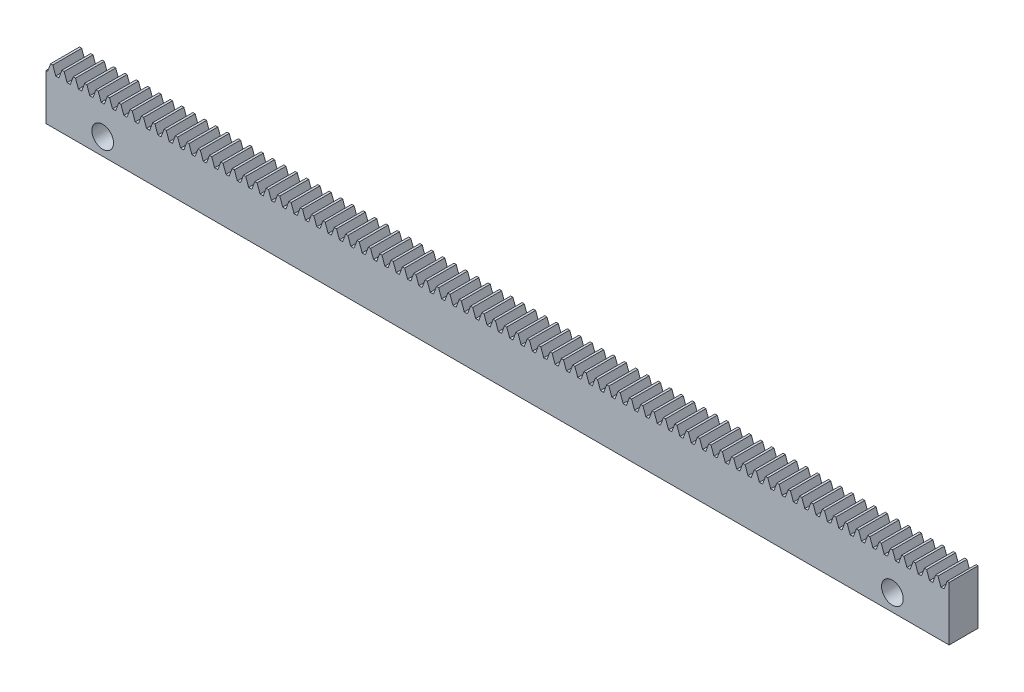
SolidWorks part; units mm, degrees
extrude "Blank" add sketch "BlankSke" against normal blind 4
sketch "BlankSke" plane through (0, 0, 0) normal (0, 0, 1) x (1, 0, 0)
  line L1 (0, 0) -> (125, 0)
  line L2 (0, 0) -> (0, 7.5)
  line L3 (0, 7.5) -> (125, 7.5)
  line L4 (125, 0) -> (125, 7.5)
  dimension "Length" = 125
  dimension "Blank_height" = 7.5
ref_plane "Plane1" through (0, 0, 0) normal (0, 0, 1) x (1, 0, 0)
ref_plane "Plane2" through (0, 0, 0) normal (0, 1, 0) x (1, 0, 0)
ref_plane "Plane3" through (0, 0, 0) normal (1, 0, 0) x (0, 0, -1)
sketch "HoldingSke" plane through (0, 0, 0) normal (0, 1, 0) x (1, 0, 0)
  line L0 (0, 0) -> (0.2783, 1.9805)
  line L1 (-15, 0) -> (100, 0) construction
  line L2 (0, 0) -> (-2.1039, 2.3779)
  line L3 (0, 0) -> (-11.863, 4.5341)
  line L4 (0, 0) -> (1.351, 8.5297)
  line L5 (0, 0) -> (-23.7986, -8.8762)
  line L6 (0, 0) -> (-10.5278, -7.1032)
  line L9 (-71.009, 38.7566) -> (46.4526, 81.5091)
  line L10 (-76.2, 2.8779) -> (-69.2, 2.8779)
  line L11 (0, 0) -> (-4, 0)
  line L12 (-76.2, 101.6) -> (-76.181, 101.6)
  line L13 (24.9733, 27.94) -> (52.9518, 28.4284)
  line L14 (24.9733, 27.94) -> (24.9743, 27.94)
  line L15 (24.9733, 27.94) -> (100.4006, 29.5858)
  circle A0 centre (0, 0) radius 19.05
  circle A1 centre (0, 0) radius 3.5
  circle A2 centre (0, 0) radius 12.7
  dimension "MPH" = 7
  dimension "Diameter" = 38.1
  dimension "Num_teeth" = 81
  dimension "Pitch" = 2
  dimension "Show_teeth" = 998
  dimension "Thickness" = 12.7
  dimension "Ap" = 20
  dimension "Pitch_height" = 7
  dimension "Width" = 4
  dimension "Backlash" = 0.019
  dimension "Addendum_fac" = 1
  dimension "Dedendum_fac" = 1.25
  dimension "Clearance_fac" = 0.25
  dimension "Dedendum_add" = 0.001
  dimension "Length" = 125
  dimension "Module" = 0.5
sketch "TooCutSkeIll" plane through (0, 0, 0) normal (0, 0, 1) x (1, 0, 0)
  line L0 (-0.6269, 7.4868) -> (-0.2524, 6.4579)
  line L1 (-0.134, 6.375) -> (0.134, 6.375)
  line L2 (0.2524, 6.4579) -> (0.6269, 7.4868)
  line L3 (125, 7.5) -> (0, 7.5) construction
  line L4 (0, 0) -> (0, 64.897) construction
  line L5 (-13.208, 7) -> (12.954, 7) construction
  line L6 (0, 0) -> (125, 0) construction
  line L7 (0.4497, 7) -> (0.4497, 48.7463) construction
  line L8 (-0.4497, 7) -> (-0.4497, 48.7463) construction
  line L9 (0.6457, 7.5) -> (0.6457, 7.5254)
  line L10 (-0.6457, 7.5) -> (-0.6457, 7.5254)
  line L11 (-0.6457, 7.5254) -> (0.6457, 7.5254)
  arc A0 (0.134, 6.375) -> (0.2524, 6.4579) centre (0.134, 6.501) ccw
  arc A1 (-0.2524, 6.4579) -> (-0.134, 6.375) centre (-0.134, 6.501) ccw
  arc A2 (0.6457, 7.5) -> (0.6269, 7.4868) centre (0.6457, 7.48) ccw
  arc A3 (-0.6269, 7.4868) -> (-0.6457, 7.5) centre (-0.6457, 7.48) ccw
  dimension "Pitch_height" = 7
  dimension "Addendum_plus" = 0.5254
  dimension "Pressure_angle" = 20
  dimension "Gap_width" = 0.8994
  dimension "Dedendum" = 0.625
extrude "ToothCutIll" [suppressed] cut sketch "TooCutSkeIll" against normal through all
sketch "TooCutSkeSim" plane through (0, 0, 0) normal (0, 0, 1) x (1, 0, 0)
  line L0 (0.2222, 6.375) -> (-0.2222, 6.375)
  line L1 (0.6409, 7.5254) -> (0.2222, 6.375)
  line L2 (0, 17.4625) -> (0, 53.467) construction
  line L3 (0.6409, 7.5254) -> (-0.6409, 7.5254)
  line L6 (-0.6409, 7.5254) -> (-0.2222, 6.375)
  line L9 (-0.4497, 7) -> (0.4497, 7) construction
  line L10 (0, 0) -> (125, 0) construction
  line L11 (0.4497, 7) -> (0.4497, 53.467) construction
  line L12 (-0.4497, 7) -> (-0.4497, 53.467) construction
  dimension "Pitch_height" = 7
  dimension "Addendum_plus" = 0.5254
  dimension "Pressure_angle" = 20
  dimension "Gap_width" = 0.8994
  dimension "Dedendum" = 0.625
extrude "ToothCutSim" cut sketch "TooCutSkeSim" against normal through all
pattern_linear "TeethCuts" count 80 spacing 1.5708 along (1, 0, 0) of "ToothCutIll", "ToothCutSim"
sketch "Sketch1" plane through (0, 0, -4) normal (0, 0, -1) x (-1, 0, 0)
  line L0 (0, 6.375) -> (0, 0) construction
  line L1 (-125, 0) -> (-125, 7.5) construction
  line L2 (0, 0) -> (-125, 0) construction
  circle A0 centre (-7.85, 2.35) radius 1.5
  circle A1 centre (-117.15, 2.35) radius 1.5
  dimension "D1" = 3
  dimension "D2" = 3
  dimension "D3" = 7.85
  dimension "D4" = 7.85
  dimension "D5" = 2.35
  dimension "D6" = 2.35
extrude "Cut-Extrude1" cut sketch "Sketch1" against normal through all
equation "' \"Module@HoldingSke\" = 6.35"
equation "' \"Num_teeth@HoldingSke\" = 12"
equation "' \"Ap@HoldingSke\" =  20"
equation "' \"Ap@HoldingSke\" = 20"
equation "' \"Width@HoldingSke\" = 0.25 * 25.4"
equation "' \"Show_teeth@HoldingSke\" = 500"
equation "' \"Backlash@HoldingSke\" = 0.009 * 25.4"
equation "' \"Addendum_fac@HoldingSke\" = 1.0"
equation "' \"Dedendum_fac@HoldingSke\" = 1.25"
equation "' \"Dedendum_add@HoldingSke\" = 0.00005 * 25.4"
equation "' \"Clearance_fac@HoldingSke\" = 0.25"
equation "' \"Pitch_height@HoldingSke\" = 1 * 25.4"
equation "' \"Length@HoldingSke\" = 4.71 * 25.4"
equation "\"Pitch@HoldingSke\" = 1 / \"Module@HoldingSke\""
equation "\"MPH@HoldingSke\" = \"Dedendum_fac@HoldingSke\" / \"Pitch@HoldingSke\" + 2 * \"Dedendum_add@HoldingSke\" + 0.002 * 25.4"
equation "\"MPH@HoldingSke\" = ((sgn( \"MPH@HoldingSke\" - \"Pitch_height@HoldingSke\")+1)*( \"MPH@HoldingSke\" - \"Pitch_height@HoldingSke\"))/2 + \"Pitch_height@HoldingSke\""
equation "\"Blank_height@BlankSke\" = \"Pitch_height@HoldingSke\" + \"Addendum_fac@HoldingSke\"  / \"Pitch@HoldingSke\" "
equation "\"Length@BlankSke\" =  \"Length@HoldingSke\""
equation "\"Face_width@Blank\" = \"Width@HoldingSke\""
equation "\"Pressure_angle@TooCutSkeIll\" = \"Ap@HoldingSke\""
equation "\"Addendum_plus@TooCutSkeIll\" =  \"Addendum_fac@HoldingSke\"  / \"Pitch@HoldingSke\" + 0.001 *25.4"
equation "\"Dedendum@TooCutSkeIll\" = \"Dedendum_fac@HoldingSke\"  / \"Pitch@HoldingSke\""
equation "\"Pitch_height@TooCutSkeIll\" =  \"MPH@HoldingSke\""
equation "\"Gap_width@TooCutSkeIll\" = 3.14159265 / 2 / \"Pitch@HoldingSke\" + 6 * \"Backlash@HoldingSke\""
equation "\"Pressure_angle@TooCutSkeSim\" = \"Ap@HoldingSke\""
equation "\"Addendum_plus@TooCutSkeSim\" =  \"Addendum_fac@HoldingSke\"  / \"Pitch@HoldingSke\" + 0.001 * 25.4"
equation "\"Dedendum@TooCutSkeSim\" = \"Dedendum_fac@HoldingSke\"  / \"Pitch@HoldingSke\""
equation "\"Pitch_height@TooCutSkeSim\" =  \"MPH@HoldingSke\""
equation "\"Gap_width@TooCutSkeSim\" = 3.14159265 / 2 / \"Pitch@HoldingSke\" + 6 * \"Backlash@HoldingSke\""
equation "\"Root_fillet@TooCutSkeIll\" = \"Clearance_fac@HoldingSke\" / \"Pitch@HoldingSke\" + \"Dedendum_add@HoldingSke\""
equation "\"Break_rad@TooCutSkeIll\" = 0.02 / \"Pitch@HoldingSke\" * 2"
equation "\"Linear_pitch@TeethCuts\" = 3.14159265 / \"Pitch@HoldingSke\""
equation "\"Num_teeth@HoldingSke\" = int( ( \"Length@HoldingSke\" + 0 ) / (3.14159265 / \"Pitch@HoldingSke\")) + 0.9999  + 1"
equation " \"Num_teeth@TeethCuts\" = int( \"Show_teeth@HoldingSke\" ) + 1"
equation " \"Num_teeth@TeethCuts\" = ((sgn( \"Num_teeth@TeethCuts\" - \"Num_teeth@HoldingSke\" )-1)*( \"Num_teeth@TeethCuts\" - \"Num_teeth@HoldingSke\" ))/-2+ \"Num_teeth@HoldingSke\""
equation " \"Num_teeth@TeethCuts\" = ((sgn( \"Num_teeth@TeethCuts\" - 2.0)+1)*( \"Num_teeth@TeethCuts\" - 2.0))/2 +2.0"
equation "\"D5@Sketch1\"=1.5+0.85"
equation "\"D6@Sketch1\"=1.5+0.85"
